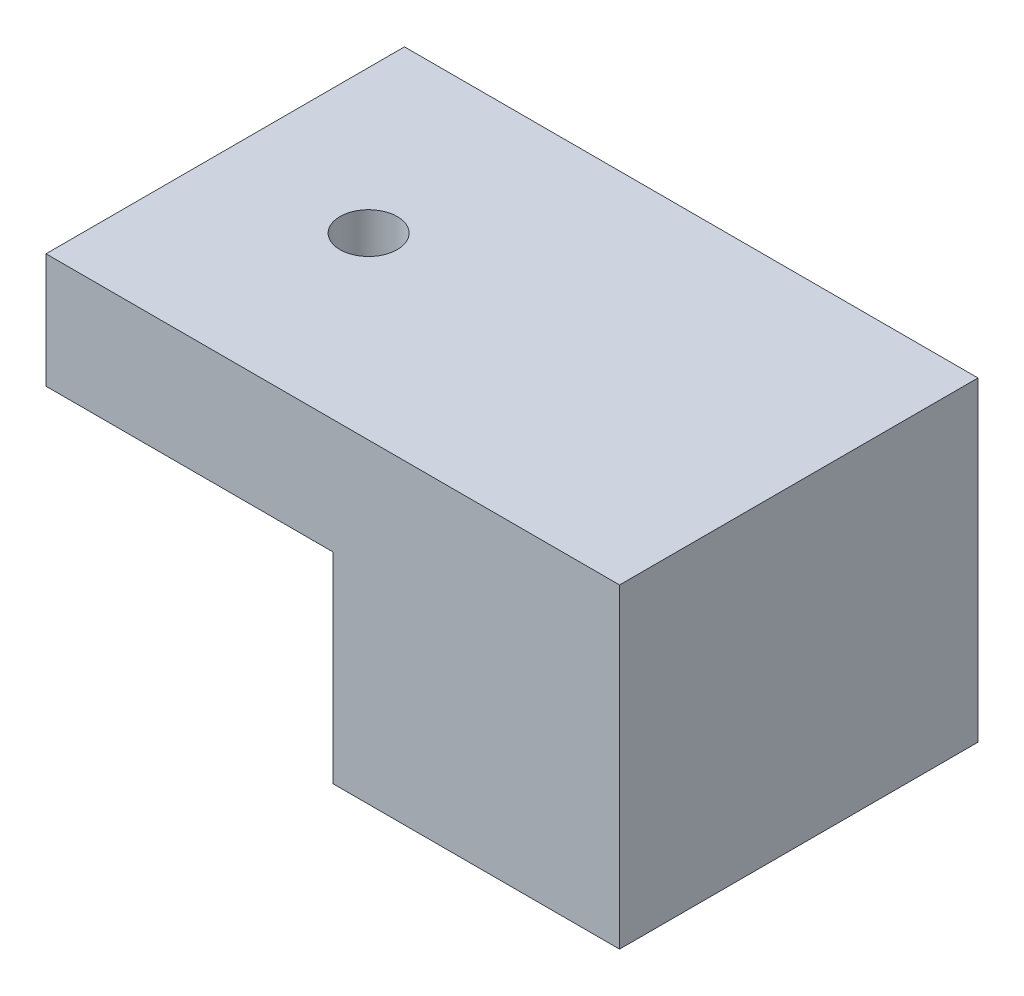
SolidWorks part; units mm, degrees
ref_plane "Plan de face" through (0, 0, 0) normal (0, 0, 1) x (1, 0, 0)
ref_plane "Plan de dessus" through (0, 0, 0) normal (0, 1, 0) x (1, 0, 0)
ref_plane "Plan de droite" through (0, 0, 0) normal (1, 0, 0) x (0, 0, -1)
sketch "Esquisse1" plane through (0, 0, 0) normal (0, 0, 1) x (1, 0, 0)
  line L0 (0, 0) -> (20, 0)
  line L1 (20, 0) -> (20, -14)
  line L2 (20, -14) -> (40, -14)
  line L3 (40, -14) -> (40, 8)
  line L4 (40, 8) -> (0, 8)
  line L5 (0, 8) -> (0, 0)
  dimension "D1" = 14
  dimension "D2" = 20
  dimension "D3" = 20
  dimension "D4" = 8
extrude "Boss.-Extru.1" add sketch "Esquisse1" along normal blind 25
sketch "Esquisse2" plane through (0, 0, 0) normal (0, -1, 0) x (1, 0, 0)
  line L0 (0, 25) -> (20, 25) construction
  line L1 (0, 25) -> (0, 0) construction
  circle A0 centre (10, 12.5) radius 2
  point P2 (0, 0)
  point P5 (10, 25)
  point P6 (0, 0)
  point P9 (0, 12.5)
  dimension "D1" = 4
extrude "Enlèv. mat.-Extru.1" cut sketch "Esquisse2" against normal through all both and the other way through all
